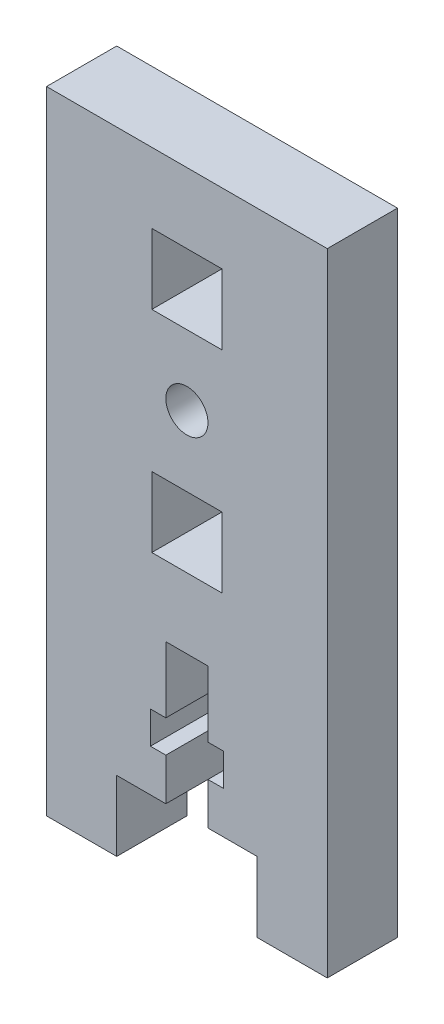
SolidWorks part; units mm, degrees
ref_plane "Front Plane" through (0, 0, 0) normal (0, 0, 1) x (1, 0, 0)
ref_plane "Top Plane" through (0, 0, 0) normal (0, 1, 0) x (1, 0, 0)
ref_plane "Right Plane" through (0, 0, 0) normal (1, 0, 0) x (0, 0, -1)
sketch "Sketch1" plane through (0, 0, 0) normal (0, 0, 1) x (1, 0, 0)
  line L0 (10, 0) -> (10, 11.2208) construction
  line L1 (0, 0) -> (20, 0) construction
  line L2 (0, 0) -> (0, 40)
  line L3 (0, 40) -> (20, 40)
  line L4 (20, 0) -> (20, 40)
  line L5 (8.5, 0) -> (5, 0)
  line L6 (5, -5) -> (0, -5)
  line L7 (0, -5) -> (0, 0)
  line L8 (5, -5) -> (5, 0)
  line L9 (11.5, 0) -> (15, 0)
  line L10 (15, 0) -> (15, -5)
  line L11 (15, -5) -> (20, -5)
  line L12 (20, -5) -> (20, 0)
  line L13 (8.5, 0) -> (11.5, 0) construction
  line L14 (11.5, 0) -> (11.5, 3)
  line L15 (11.5, 5.3) -> (12.6, 5.3)
  line L16 (7.4, 3) -> (7.4, 5.3)
  line L17 (12.6, 3) -> (11.5, 3)
  line L18 (11.5, 5.3) -> (11.5, 10)
  line L19 (11.5, 10) -> (8.5, 10)
  line L20 (8.5, 10) -> (8.5, 5.3)
  line L21 (8.5, 3) -> (7.4, 3)
  line L22 (12.6, 5.3) -> (12.6, 3)
  line L23 (7.4, 5.3) -> (8.5, 5.3)
  line L24 (8.5, 3) -> (8.5, 0)
  line L25 (10, 10) -> (10, 0) construction
  line B0 (10, 20) -> (10, 30) construction
  line B1 (7.5, 20) -> (7.5, 15)
  line B2 (7.5, 20) -> (12.5, 20)
  line B3 (12.5, 20) -> (12.5, 15)
  line B4 (7.5, 15) -> (12.5, 15)
  line B5 (7.5, 30) -> (7.5, 35)
  line B6 (7.5, 30) -> (12.5, 30)
  line B7 (12.5, 30) -> (12.5, 35)
  line B8 (7.5, 35) -> (12.5, 35)
  line B9 (10, 25) -> (3.0276, 25) construction
  circle B10 centre (10, 25) radius 1.5
  dimension "20" = 40
  dimension "D2" = 25
  dimension "D3" = 10
  dimension "D4" = 5
  dimension "D5" = 5
  dimension "D6" = 5.2
  dimension "D7" = 3
  dimension "D8" = 2.3
  dimension "D9" = 3
  dimension "D10" = 10
sketch_block_instance "Trou M3 plots 5mm-1"
sketch_block "Trou M3 plots 5mm" parameters "D2"=3, "D1"=5, "D3"=5, "D4"=10
extrude "Boss-Extrude1" add sketch "Sketch1" along normal blind 5
